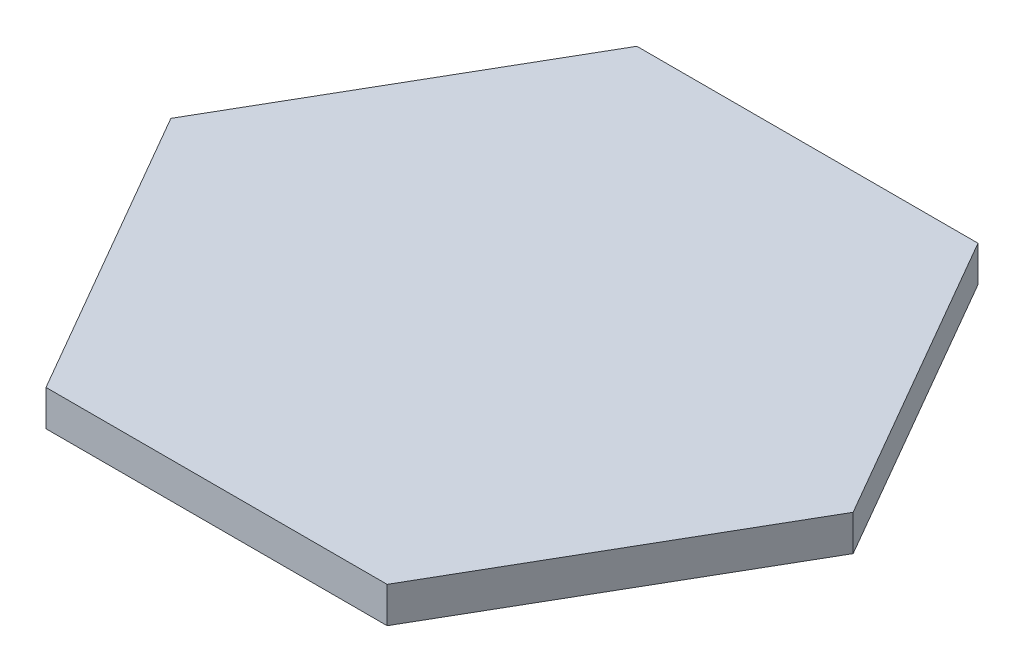
SolidWorks part; units mm, degrees
material "Pine"
ref_plane "Front Plane" through (0, 0, 0) normal (0, 0, 1) x (1, 0, 0)
ref_plane "Top Plane" through (0, 0, 0) normal (0, 1, 0) x (1, 0, 0)
ref_plane "Right Plane" through (0, 0, 0) normal (1, 0, 0) x (0, 0, -1)
sketch "Sketch1" plane through (0, 0, 0) normal (0, 1, 0) x (1, 0, 0)
  line L1 (71.4, 0) -> (35.7, 61.8342)
  line L2 (35.7, 61.8342) -> (-35.7, 61.8342)
  line L3 (-35.7, 61.8342) -> (-71.4, 0)
  line L4 (-71.4, 0) -> (-35.7, -61.8342)
  line L5 (-35.7, -61.8342) -> (35.7, -61.8342)
  line L6 (35.7, -61.8342) -> (71.4, 0)
  circle A0 centre (0, 0) radius 71.4 construction
  dimension "D1" = 71.4
extrude "Boss-Extrude1" add sketch "Sketch1" along normal blind 7.5
